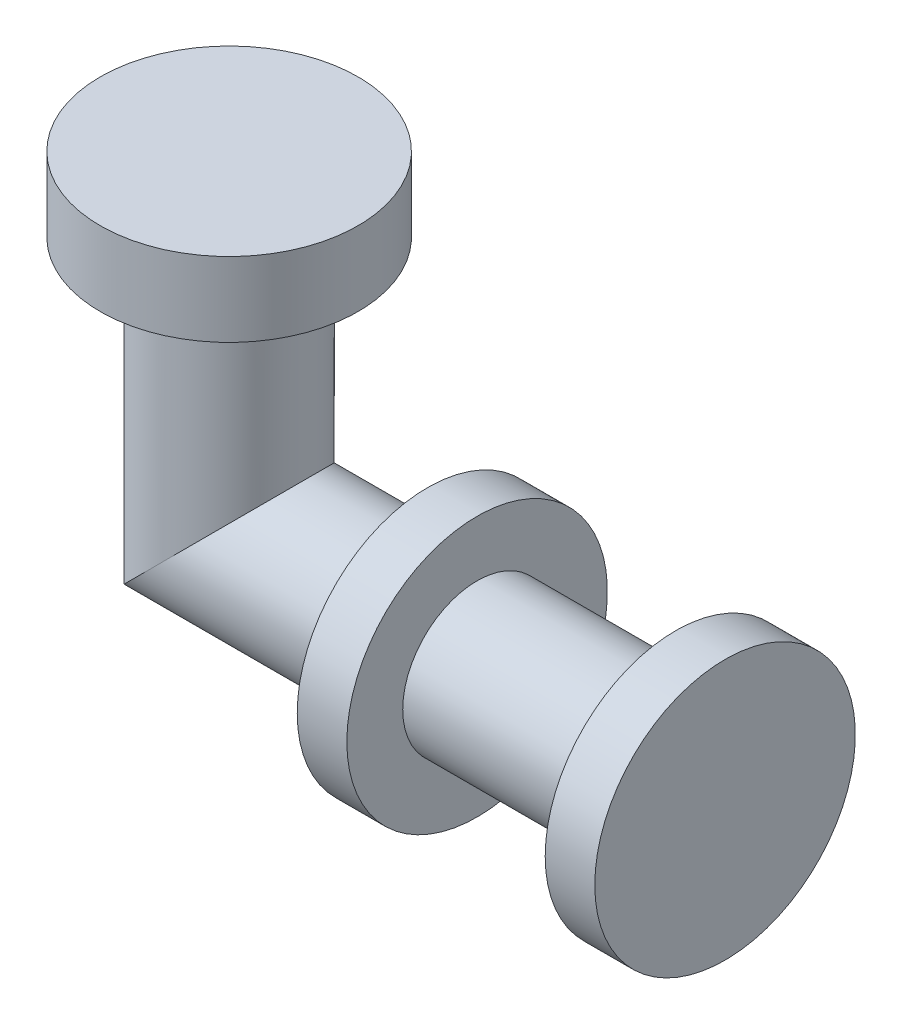
SolidWorks part; units mm, degrees
ref_plane "Front Plane" through (0, 0, 0) normal (0, 0, 1) x (1, 0, 0)
ref_plane "Top Plane" through (0, 0, 0) normal (0, 1, 0) x (1, 0, 0)
ref_plane "Right Plane" through (0, 0, 0) normal (1, 0, 0) x (0, 0, -1)
sketch "Sketch1" plane through (0, 0, 0) normal (0, 0, 1) x (1, 0, 0)
  line L0 (0, 82.55) -> (0, 0)
  line L1 (0, 0) -> (127, 0)
  dimension "D1" = 82.55
  dimension "D2" = 127
ref_plane "Plane1" through (127, 0, 0) normal (1, 0, 0) x (0, 0, -1)
sketch "Sketch2" plane through (127, 0, 0) normal (1, 0, 0) x (0, 0, -1)
  circle A0 centre (0, 0) radius 19.05
  dimension "D1" = 38.1
sweep "Sweep1" add profiles "Sketch2" path "Sketch1"
sketch "Sketch3" plane through (0, 82.55, 0) normal (0, 1, 0) x (1, 0, 0)
  circle A0 centre (0, 0) radius 33.02
  dimension "D1" = 66.04
extrude "Boss-Extrude1" add sketch "Sketch3" against normal blind 19.05
sketch "Sketch4" plane through (0, 0, 0) normal (0, 0, 1) x (1, 0, 0)
  line L0 (0, 0) -> (127, 0) construction
  line L1 (0, 0) -> (127, 0) construction
  line L2 (127, 19.05) -> (127, 33.3635)
  line L3 (127, 33.3635) -> (114.3, 33.3635)
  line L4 (114.3, 33.3635) -> (114.3, 19.05)
  line L5 (127, 19.05) -> (19.05, 19.05) construction
  line L6 (114.3, 19.05) -> (63.5, 19.05) construction
  line L7 (63.5, 19.05) -> (63.5, 33.3635)
  line L8 (63.5, 33.3635) -> (50.8, 33.3635)
  line L9 (50.8, 33.3635) -> (50.8, 19.05)
  line L10 (50.8, 19.05) -> (63.5, 19.05)
  line L11 (127, 19.05) -> (114.3, 19.05)
  line L12 (0, 82.55) -> (0, 0) construction
  line L13 (127, -19.05) -> (127, 19.05) construction
  point P9 (88.9, 19.05)
  dimension "D1" = 19.05
  dimension "D2" = 19.05
  dimension "D3" = 19.05
  dimension "D4" = 19.05
  dimension "D5" = 88.9
  dimension "D6" = 12.7
  dimension "D7" = 12.7
revolve "Revolve1" add sketch "Sketch4" angle 360 about L1
